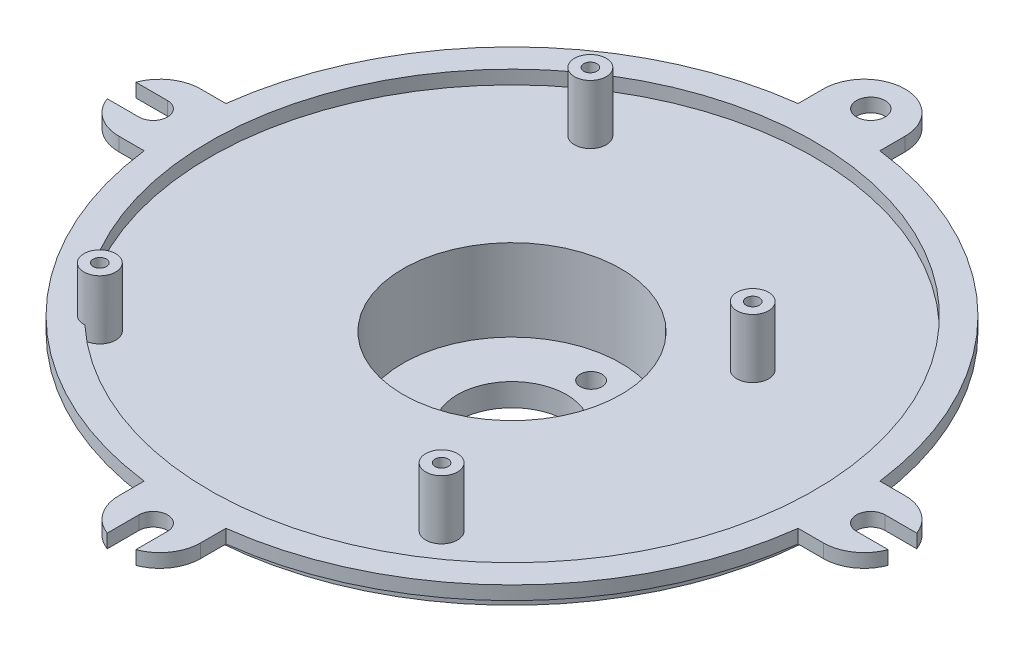
SolidWorks part; units mm, degrees
ref_plane "Front Plane" through (0, 0, 0) normal (0, 0, 1) x (1, 0, 0)
ref_plane "Top Plane" through (0, 0, 0) normal (0, 1, 0) x (1, 0, 0)
ref_plane "Right Plane" through (0, 0, 0) normal (1, 0, 0) x (0, 0, -1)
other "Configuration Table"
sketch "Sketch1" plane through (0, 0, 0) normal (0, 1, 0) x (1, 0, 0)
  circle A0 centre (0, 0) radius 69.55
  dimension "D1" = 139.1
extrude "Boss-Extrude1" add sketch "Sketch1" along normal blind 3
sketch "Sketch2" plane through (0, 3, 0) normal (0, 1, 0) x (1, 0, 0)
  line L0 (69.55, 0) -> (72.55, 0) construction
  line L1 (66.55, 0) -> (69.55, 0) construction
  circle A0 centre (0, 0) radius 72.55
  circle A1 centre (0, 0) radius 69.55 construction
  circle A2 centre (0, 0) radius 69.55 construction
  circle A3 centre (0, 0) radius 66.55
  dimension "D1" = 3
  dimension "D2" = 3
extrude "Boss-Extrude2" add sketch "Sketch2" along normal blind 3
sketch "Sketch3" plane through (0, 3, 0) normal (0, 1, 0) x (1, 0, 0)
  circle A0 centre (-45.5, -45.25) radius 1.6 construction
  circle A1 centre (30.25, -45.75) radius 1.6 construction
  circle A2 centre (33.75, 19.25) radius 1.6 construction
  circle A3 centre (-28.75, 46) radius 1.6 construction
  circle A4 centre (-45.5, -45.25) radius 1.6
  circle A5 centre (30.25, -45.75) radius 1.6
  circle A6 centre (33.75, 19.25) radius 1.6
  circle A7 centre (-28.75, 46) radius 1.6
sketch "Sketch4" plane through (0, 3, 0) normal (0, 1, 0) x (1, 0, 0)
  circle A0 centre (33.75, 19.25) radius 1.6 construction
  circle A1 centre (30.25, -45.75) radius 1.6 construction
  circle A2 centre (-45.5, -45.25) radius 1.6 construction
  circle A3 centre (-28.75, 46) radius 1.6 construction
  circle A4 centre (33.75, 19.25) radius 1.6 construction
  circle A5 centre (30.25, -45.75) radius 1.6 construction
  circle A6 centre (-45.5, -45.25) radius 1.6 construction
  circle A7 centre (-28.75, 46) radius 1.6 construction
  circle A8 centre (-28.75, 46) radius 3.5
  circle A9 centre (33.75, 19.25) radius 3.5
  circle A10 centre (30.25, -45.75) radius 3.5
  circle A11 centre (-45.5, -45.25) radius 3.5
  circle A12 centre (-28.75, 46) radius 1.45
  circle A13 centre (33.75, 19.25) radius 1.45
  circle A14 centre (30.25, -45.75) radius 1.45
  circle A15 centre (-45.5, -45.25) radius 1.45
  dimension "D1" = 7
  dimension "D2" = 2.9
extrude "Boss-Extrude3" add sketch "Sketch4" along normal offset from surface (13 mm away) 10 up to face at (0, 6, 72.55) offset beyond the face yes
sketch "Sketch5" plane through (0, 3, 0) normal (0, 1, 0) x (1, 0, 0)
  line L0 (0, 0) -> (0, -72.55) construction
  line L1 (-9, -69.55) -> (9, -69.55)
  line L2 (-9, -69.55) -> (-9, -77.55)
  line L3 (9, -69.55) -> (9, -77.55)
  line L4 (0, 0) -> (0, -79) construction
  circle A0 centre (0, 0) radius 72.55 construction
  arc A4 (-9, -77.55) -> (9, -77.55) centre (0, -77.55) ccw
  circle A5 centre (0, -79) radius 3.15
  point P9 (0, -69.55)
  dimension "D5" = 6.3
  dimension "D1" = 18
  dimension "D2" = 8
  dimension "D3" = 3
  dimension "D4" = 79
extrude "Boss-Extrude4" add sketch "Sketch5" along normal up to surface (3 mm away) up to face at (0, 6, 72.55)
pattern_circular "CirPattern1" count 4 over 360 about axis through (0, 0, 0) along (0, 1, 0) of "Boss-Extrude4"
sketch "Sketch6" plane through (0, 0, 0) normal (0, -1, 0) x (1, 0, 0)
  circle A0 centre (0, 0) radius 27.5
  dimension "D1" = 55
extrude "Boss-Extrude5" add sketch "Sketch6" along normal blind 20
sketch "Sketch7" plane through (0, -20, 0) normal (0, -1, 0) x (1, 0, 0)
  circle A0 centre (0, 0) radius 12
  dimension "D1" = 24
extrude "Cut-Extrude1" cut sketch "Sketch7" against normal through all
sketch "Sketch8" plane through (0, 3, 0) normal (0, 1, 0) x (1, 0, 0)
  circle A0 centre (0, 0) radius 24
  dimension "D1" = 48
extrude "Cut-Extrude2" cut sketch "Sketch8" against normal blind 18
sketch "Sketch9" plane through (0, -15, 0) normal (0, 1, 0) x (1, 0, 0)
  line L0 (0, 0) -> (0, 17.41) construction
  line L1 (0, 0) -> (-15.0775, -8.705) construction
  line L2 (0, 0) -> (15.0775, -8.705) construction
  circle A0 centre (0, 0) radius 17.41 construction
  circle A1 centre (0, 17.41) radius 2.4
  circle A2 centre (-15.0775, -8.705) radius 2.4
  circle A3 centre (15.0775, -8.705) radius 2.4
  dimension "D1" = 34.82
  dimension "D4" = 4.8
  dimension "D2" = 120
  dimension "D3" = 120
extrude "Cut-Extrude3" cut sketch "Sketch9" against normal through all contours A2
sketch "Sketch10" plane through (0, 6, 0) normal (0, 1, 0) x (1, 0, 0)
  line L0 (-79, 3.15) -> (-98.9358, 3.15)
  line L1 (-98.9358, 3.15) -> (-98.9358, -3.15)
  line L2 (-98.9358, -3.15) -> (-79, -3.15)
  line L3 (-79, -3.15) -> (-79, 3.15)
  line L4 (-3.15, -79) -> (-3.15, -98.9358)
  line L5 (-3.15, -79) -> (3.15, -79)
  line L6 (3.15, -79) -> (3.15, -98.9358)
  line L7 (3.15, -98.9358) -> (-3.15, -98.9358)
  line L8 (79, 3.15) -> (79, -3.15)
  line L9 (79, -3.15) -> (98.9358, -3.15)
  line L10 (98.9358, -3.15) -> (98.9358, 3.15)
  line L11 (98.9358, 3.15) -> (79, 3.15)
  circle A0 centre (79, 0) radius 3.15 construction
  circle A1 centre (0, -79) radius 3.15 construction
  circle A2 centre (-79, 0) radius 3.15 construction
  circle A3 centre (79, 0) radius 3.15 construction
  circle A4 centre (0, -79) radius 3.15 construction
  circle A5 centre (-79, 0) radius 3.15 construction
extrude "Cut-Extrude4" cut sketch "Sketch10" against normal through all
sketch "Sketch11" plane through (0, 0, 0) normal (1, 0, 0) x (0, 0, -1)
  line L0 (27.5, 0) -> (27.5, -5)
  line L1 (27.5, -20) -> (27.5, 0) construction
  line L2 (27.5, 0) -> (32.5, 0)
  line L3 (-69.55, 0) -> (69.55, 0) construction
  arc A0 (27.5, -5) -> (32.5, 0) centre (27.5, 0) ccw
  point P9 (32.0192, -0.1818)
  dimension "D1" = 5
ref_axis "Axis1" through (0, -20, 0) along (0, 1, 0)
revolve "Revolve1" add sketch "Sketch11" angle 360 about axis through (0, -20, 0) along (0, 1, 0)
